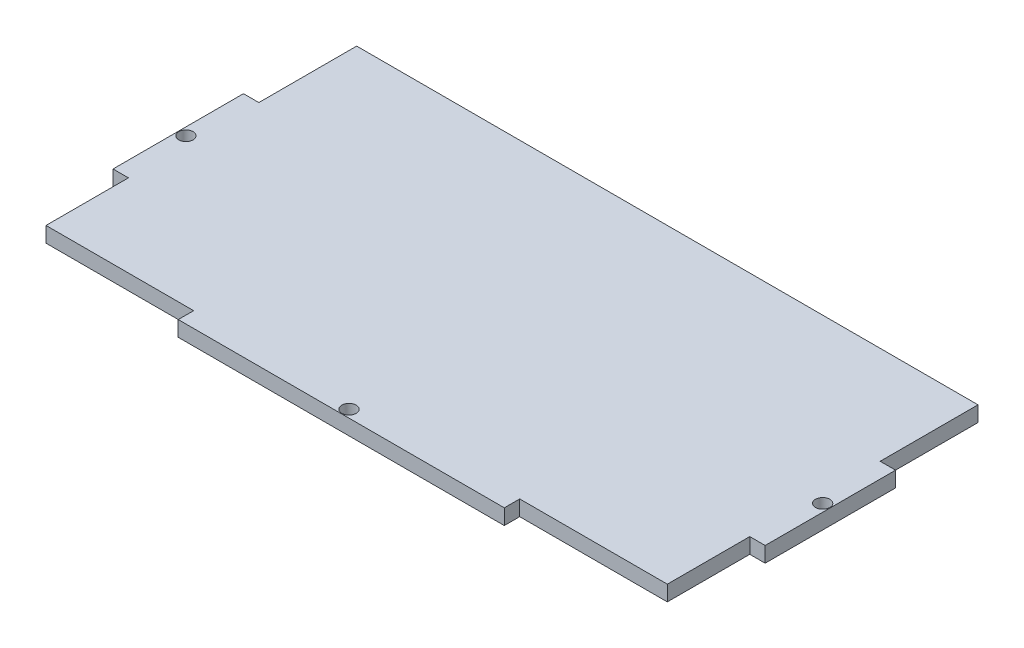
SolidWorks part; units mm, degrees
ref_plane "Front Plane" through (0, 0, 0) normal (0, 0, 1) x (1, 0, 0)
ref_plane "Top Plane" through (0, 0, 0) normal (0, 1, 0) x (1, 0, 0)
ref_plane "Right Plane" through (0, 0, 0) normal (1, 0, 0) x (0, 0, -1)
sketch "Sketch1" plane through (0, 0, 0) normal (0, 1, 0) x (1, 0, 0)
  line L1 (-63.5, -31.75) -> (63.5, -31.75)
  line L2 (-63.5, -31.75) -> (-63.5, 31.75)
  line L3 (-63.5, 31.75) -> (63.5, 31.75)
  line L4 (63.5, -31.75) -> (63.5, 31.75)
  line L5 (-63.5, -31.75) -> (63.5, 31.75) construction
  line L6 (-63.5, 31.75) -> (63.5, -31.75) construction
  point P0 (0, 0)
  dimension "D1" = 127
  dimension "10" = 63.5
extrude "Boss-Extrude1" add sketch "Sketch1" along normal blind 2.9972
sketch "Sketch2" plane through (0, 2.9972, 0) normal (0, 1, 0) x (1, 0, 0)
  line L0 (63.5, -31.75) -> (31.75, -31.75)
  line L9 (-63.5, 31.75) -> (-60.5028, 31.75)
  line L14 (-63.5, 31.75) -> (-63.5, 12.7)
  line L24 (-63.5, -31.75) -> (-31.75, -31.75)
  line L25 (-63.5, -31.75) -> (-63.5, -28.7528)
  line L26 (-60.5028, -28.7528) -> (-31.75, -28.7528)
  line L27 (-31.75, -31.75) -> (-31.75, -28.7528)
  line L30 (-63.5, 12.7) -> (-60.5028, 12.7)
  line L54 (31.75, -31.75) -> (31.75, -28.7528)
  line L74 (-60.5028, 31.75) -> (-60.5028, 12.7)
  line L109 (0, 31.75) -> (0, -31.75) construction
  line L115 (63.5, 31.75) -> (-63.5, 31.75) construction
  line L128 (-63.5, -31.75) -> (63.5, -31.75) construction
  line L159 (-63.5, -28.7528) -> (-63.5, -12.7)
  line L160 (-63.5, -12.7) -> (-60.5028, -12.7)
  line L161 (-60.5028, -28.7528) -> (-60.5028, -12.7)
  line L162 (60.5028, -28.7528) -> (31.75, -28.7528)
  line L163 (60.5028, -28.7528) -> (60.5028, -12.7)
  line L164 (63.5, -12.7) -> (60.5028, -12.7)
  line L165 (63.5, -28.7528) -> (63.5, -12.7)
  line L166 (63.5, -31.75) -> (63.5, -28.7528)
  line L167 (63.5, 12.7) -> (60.5028, 12.7)
  line L168 (60.5028, 31.75) -> (60.5028, 12.7)
  line L169 (63.5, 31.75) -> (60.5028, 31.75)
  line L170 (63.5, 31.75) -> (63.5, 12.7)
  line L171 (-63.5, 0) -> (63.5, 0) construction
  line L172 (-63.5, 31.75) -> (-63.5, -31.75) construction
  line L173 (63.5, -31.75) -> (63.5, 31.75) construction
  circle A7 centre (0, -30.2514) radius 1.397
  circle A8 centre (-62.0014, 0) radius 1.397
  circle A9 centre (62.0014, 0) radius 1.397
  point P14 (0, 0)
  point P27 (-62.0014, -12.7)
  dimension "D8" = 2.794
  dimension "D5" = 2.794
  dimension "D1" = 2.9972
  dimension "D2" = 19.05
  dimension "D3" = 31.75
  dimension "D4" = 16.0528
extrude "Cut-Extrude1" cut sketch "Sketch2" against normal up to next
